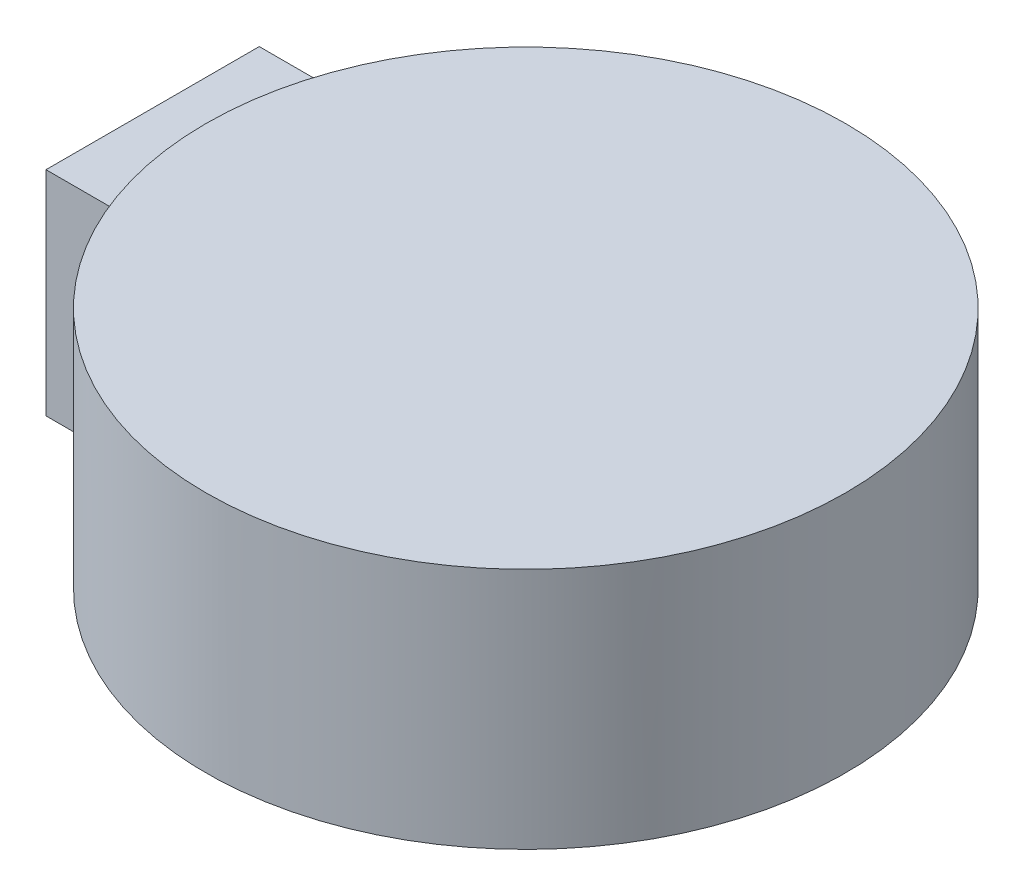
SolidWorks part; units mm, degrees
ref_plane "前视基准面" through (0, 0, 0) normal (0, 0, 1) x (1, 0, 0)
ref_plane "上视基准面" through (0, 0, 0) normal (0, 1, 0) x (1, 0, 0)
ref_plane "右视基准面" through (0, 0, 0) normal (1, 0, 0) x (0, 0, -1)
sketch "草图1" plane through (0, 0, 0) normal (0, 1, 0) x (1, 0, 0)
  circle A0 centre (0, 0) radius 60
  circle A1 centre (0, 0) radius 40
  dimension "D1" = 80
  dimension "D2" = 120
extrude "凸台-拉伸1" add sketch "草图1" along normal blind 20
sketch "草图2" plane through (0, 20, 0) normal (0, 1, 0) x (1, 0, 0)
  circle A0 centre (0, 0) radius 60 construction
  circle A1 centre (0, 0) radius 60
extrude "凸台-拉伸4" add sketch "草图2" along normal blind 5
sketch "草图3" plane through (0, 0, 0) normal (1, 0, 0) x (0, 0, -1)
  line L0 (0, 0) -> (0, 25) construction
  line L1 (-20, -7.5) -> (20, -7.5)
  line L2 (-20, -7.5) -> (-20, 32.5)
  line L3 (-20, 32.5) -> (20, 32.5)
  line L4 (20, -7.5) -> (20, 32.5)
  line L5 (-20, -7.5) -> (20, 32.5) construction
  line L6 (-20, 32.5) -> (20, -7.5) construction
  line L7 (-60, 0) -> (60, 0) construction
  line L8 (60, 25) -> (-60, 25) construction
  point P0 (0, 12.5)
  dimension "D1" = 40
extrude "凸台-拉伸5" add sketch "草图3" along normal up to surface (13.4315 mm away) from offset 70 offset against normal yes
sketch "草图4" plane through (-70, 0, 0) normal (-1, 0, 0) x (0, 0, 1)
  line L0 (0, 32.5) -> (0, -7.5) construction
  line L1 (15, -2.5) -> (-15, -2.5) construction
  line L2 (15, -2.5) -> (15, 27.5) construction
  line L3 (15, 27.5) -> (-15, 27.5) construction
  line L4 (-15, -2.5) -> (-15, 27.5) construction
  line L5 (15, -2.5) -> (-15, 27.5) construction
  line L6 (15, 27.5) -> (-15, -2.5) construction
  line L7 (-20, 32.5) -> (20, 32.5) construction
  line L8 (20, -7.5) -> (-20, -7.5) construction
  circle A0 centre (-15, 27.5) radius 2.5
  circle A1 centre (15, 27.5) radius 2.5
  circle A2 centre (15, -2.5) radius 2.5
  circle A3 centre (-15, -2.5) radius 2.5
  point P0 (0, 12.5)
  dimension "D2" = 5
  dimension "D1" = 30
extrude "切除-拉伸1" cut sketch "草图4" against normal blind 5
sketch "草图5" plane through (0, 0, 0) normal (0, -1, 0) x (1, 0, 0)
  circle A0 centre (0, 0) radius 40 construction
  circle A1 centre (0, 0) radius 40
  arc A2 (-56.5685, 20) -> (-56.5685, -20) centre (0, 0) ccw
  arc A3 (-56.5685, -20) -> (-56.5685, 20) centre (0, 0) ccw
  arc A4 (-56.5685, 20) -> (-56.5685, -20) centre (0, 0) ccw
  arc A5 (-56.5685, -20) -> (-56.5685, 20) centre (0, 0) ccw
  dimension "D1" = 0
extrude "凸台-拉伸6" add sketch "草图5" along normal blind 10.5
sketch "草图6" plane through (0, 25, 0) normal (0, 1, 0) x (1, 0, 0)
  arc A2 (-56.5685, 20) -> (-56.5685, -20) centre (0, 0) ccw
  arc A3 (-56.5685, -20) -> (-56.5685, 20) centre (0, 0) ccw
  arc A4 (-56.5685, 20) -> (-56.5685, -20) centre (0, 0) ccw
  arc A5 (-56.5685, -20) -> (-56.5685, 20) centre (0, 0) ccw
  dimension "D1" = 0
extrude "凸台-拉伸7" add sketch "草图6" along normal blind 10
